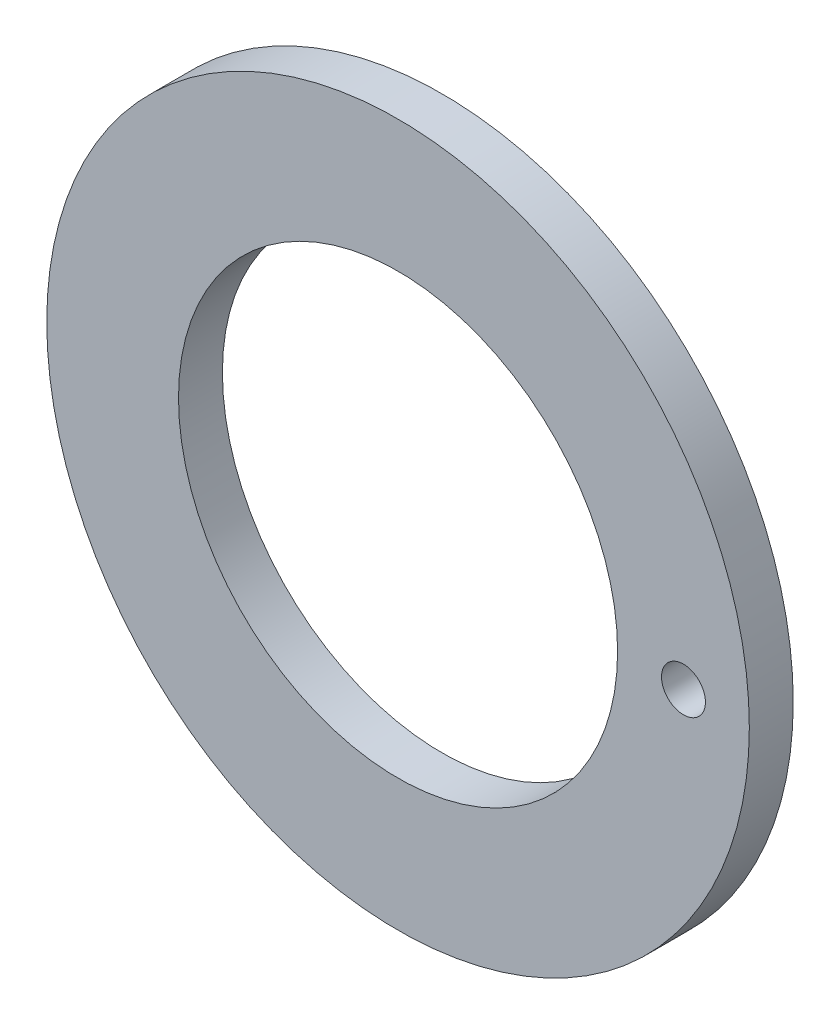
SolidWorks part; units mm, degrees
ref_plane "Front Plane" through (0, 0, 0) normal (0, 0, 1) x (1, 0, 0)
ref_plane "Top Plane" through (0, 0, 0) normal (0, 1, 0) x (1, 0, 0)
ref_plane "Right Plane" through (0, 0, 0) normal (1, 0, 0) x (0, 0, -1)
sketch "Sketch1" plane through (0, 0, 0) normal (0, 0, 1) x (1, 0, 0)
  circle A0 centre (0, 0) radius 12
  circle A1 centre (0, 0) radius 7.5
  circle A2 centre (0, 0) radius 9.75 construction
  circle A3 centre (9.75, 0) radius 0.75
  point P7 (0, -12)
  dimension "OD (d2)" = 24
  dimension "ID | For Shaft Diameter (d1)" = 15
  dimension "Circle Diameter (d4)" = 19.5
  dimension "Hole Diameter (d5)" = 1.5
sketch "Sketch2" plane through (0, 0, 0) normal (1, 0, 0) x (0, 0, -1)
  line L0 (0.75, -12) -> (-0.75, -12) construction
  point P0 (0, -12)
  point P4 (0, 0)
  dimension "Thickness" = 1.5
sketch "Sketch5" plane through (0, 0, 0) normal (0, 0, 1) x (1, 0, 0)
  circle A0 centre (0, 0) radius 7.5 construction
  circle A1 centre (0, 0) radius 12 construction
  circle A2 centre (0, 0) radius 7.5
  circle A3 centre (0, 0) radius 12
extrude "Body Extrude" add sketch "Sketch5" along normal mid plane 1.5
sketch "Sketch3" plane through (0, 0, 0) normal (0, 0, 1) x (1, 0, 0)
  circle A0 centre (9.75, 0) radius 0.75 construction
  circle A1 centre (9.75, 0) radius 0.75
extrude "Hole Cut" cut sketch "Sketch3" against normal through all both and the other way through all
equation "\"Thickness (s)@Body Extrude\"=\"Thickness@Sketch2\""
